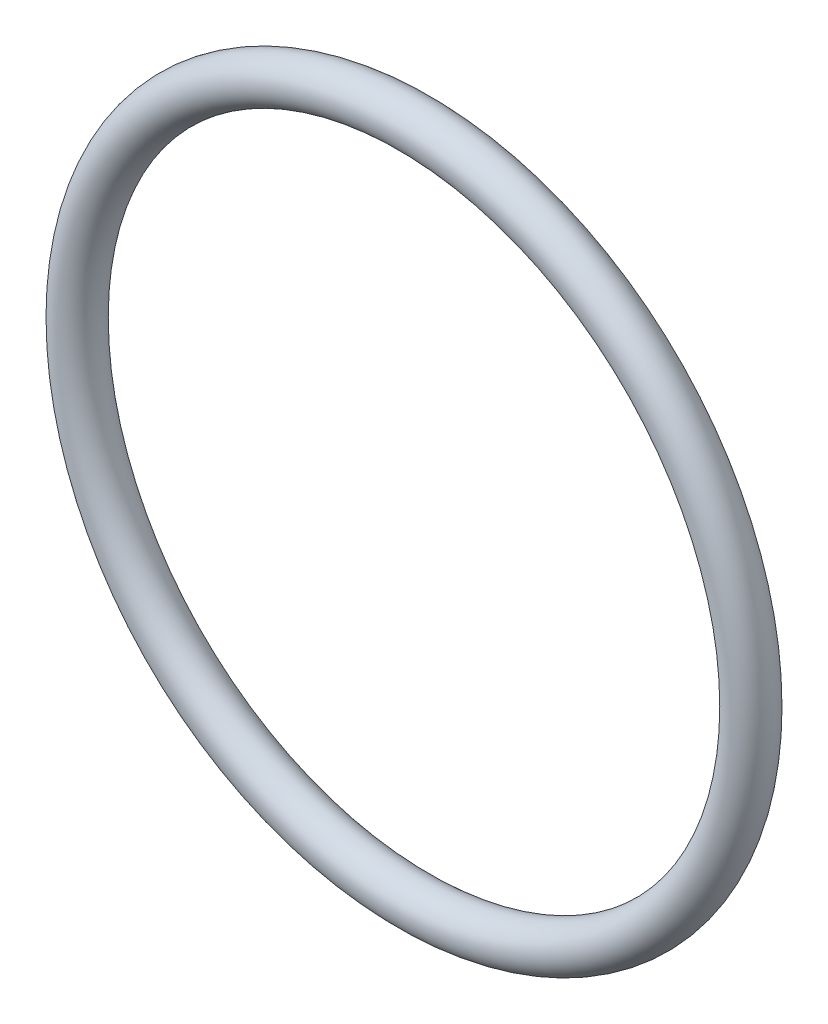
SolidWorks part; units mm, degrees
material "Silicon Rubber"
ref_plane "Front Plane" through (0, 0, 0) normal (0, 0, 1) x (1, 0, 0)
ref_plane "Top Plane" through (0, 0, 0) normal (0, 1, 0) x (1, 0, 0)
ref_plane "Right Plane" through (0, 0, 0) normal (1, 0, 0) x (0, 0, -1)
sketch "Sketch1" plane through (0, 0, 0) normal (0, 1, 0) x (1, 0, 0)
  line L0 (0, 34.8731) -> (0, -29.5759) construction
  line L1 (0, 0) -> (18.161, 0) construction
  line L2 (18.161, 0) -> (19.431, 0) construction
  circle A0 centre (19.431, 0) radius 1.27
  dimension "D1" = 18.161
  dimension "D2" = 1.27
revolve "Revolve1" add sketch "Sketch1" angle 360 about L0
